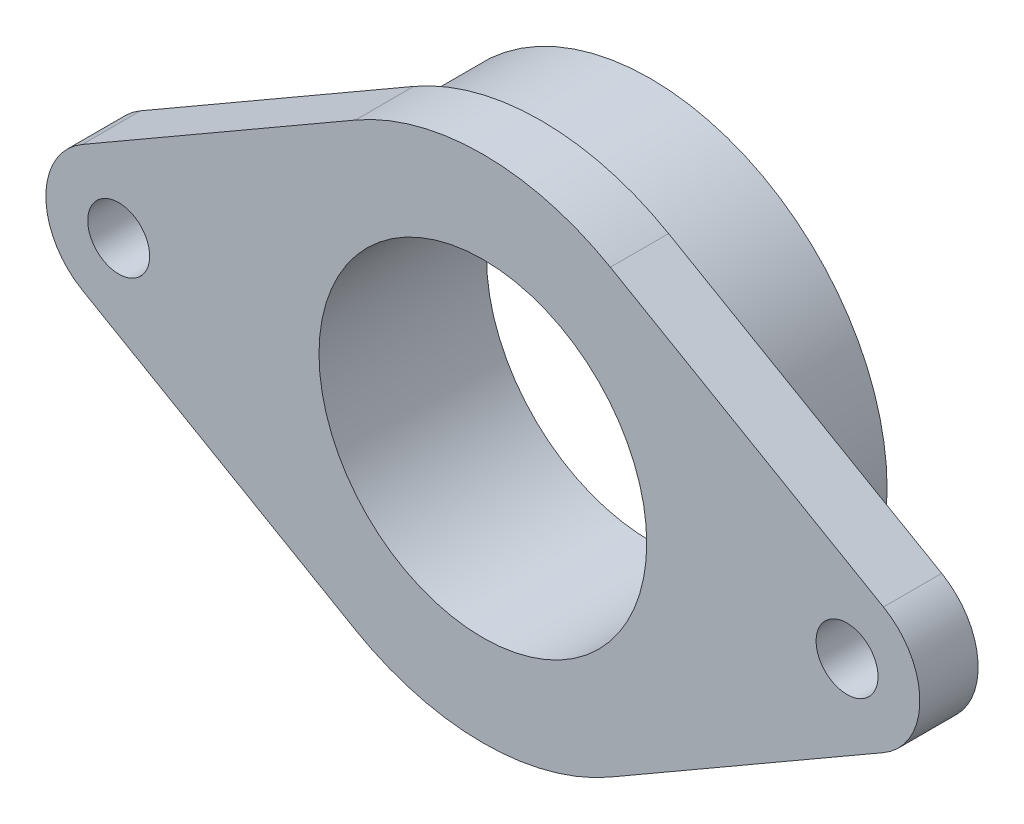
SolidWorks part; units mm, degrees
material "Malleable Cast Iron"
ref_plane "Front Plane" through (0, 0, 0) normal (0, 0, 1) x (1, 0, 0)
ref_plane "Top Plane" through (0, 0, 0) normal (0, 1, 0) x (1, 0, 0)
ref_plane "Right Plane" through (0, 0, 0) normal (1, 0, 0) x (0, 0, -1)
sketch "Sketch2" plane through (0, 0, 0) normal (0, 0, 1) x (1, 0, 0)
  line L0 (-55, 8.6603) -> (-17.5, 30.3109)
  line L1 (0, 0) -> (-17.5, 0) construction
  line L2 (0, 0) -> (0, 17.3069) construction
  line L3 (-55, -8.6603) -> (-17.5, -30.3109)
  line L4 (55, -8.6603) -> (17.5, -30.3109)
  line L5 (55, 8.6603) -> (17.5, 30.3109)
  circle A0 centre (0, 0) radius 22.5
  arc A1 (-17.5, -30.3109) -> (17.5, -30.3109) centre (0, 0) ccw
  circle A2 centre (50, 0) radius 4.25
  circle A3 centre (-50, 0) radius 4.25
  arc A4 (-55, 8.6603) -> (-55, -8.6603) centre (-50, 0) ccw
  arc A5 (55, -8.6603) -> (55, 8.6603) centre (50, 0) ccw
  arc A6 (17.5, 30.3109) -> (-17.5, 30.3109) centre (0, 0) ccw
  dimension "D2" = 45
  dimension "D3" = 8.5
  dimension "D4" = 8.5
  dimension "D5" = 50
  dimension "D6" = 50
  dimension "D7" = 20
  dimension "D8" = 20
extrude "Boss-Extrude1" add sketch "Sketch2" along normal blind 8
sketch "Sketch3" plane through (0, 0, 0) normal (0, 0, -1) x (-1, 0, 0)
  circle A0 centre (0, 0) radius 22.5 construction
  circle A1 centre (0, 0) radius 22.5
  circle A2 centre (0, 0) radius 32.5
  dimension "D1" = 65
extrude "Boss-Extrude2" add sketch "Sketch3" along normal blind 15
